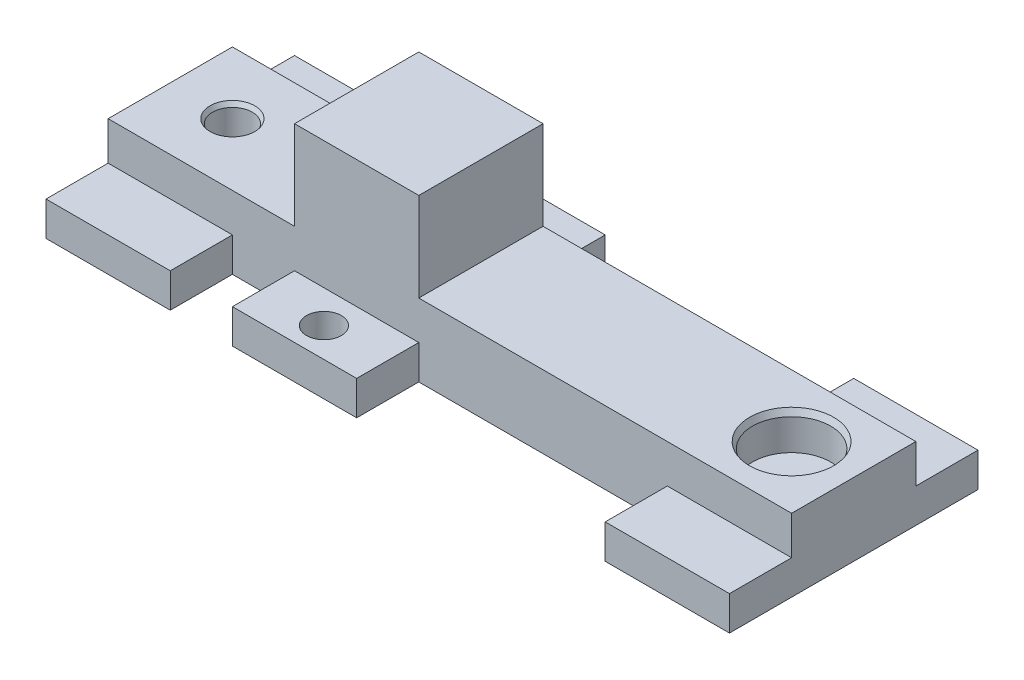
SolidWorks part; units mm, degrees
ref_plane "Front Plane" through (0, 0, 0) normal (0, 0, 1) x (1, 0, 0)
ref_plane "Top Plane" through (0, 0, 0) normal (0, 1, 0) x (1, 0, 0)
ref_plane "Right Plane" through (0, 0, 0) normal (1, 0, 0) x (0, 0, -1)
sketch "Sketch1" plane through (0, 0, 0) normal (0, 1, 0) x (1, 0, 0)
  line L1 (-20, 10) -> (35, 10)
  line L2 (-20, 10) -> (-20, -10)
  line L3 (-20, -10) -> (35, -10)
  line L4 (35, 10) -> (35, -10)
  dimension "D1" = 20
  dimension "D2" = 10
extrude "Boss-Extrude1" add sketch "Sketch1" along normal mid plane 13
sketch "Sketch2" plane through (0, 6.5, 0) normal (0, 1, 0) x (1, 0, 0)
  line L1 (35, 10) -> (-20, 10) construction
  line L2 (-20, -10) -> (35, -10) construction
  line L3 (-5, -10) -> (-20, -10)
  line L4 (-20, -10) -> (-20, 10)
  line L5 (-20, 10) -> (-5, 10)
  line L7 (5, -10) -> (35, -10)
  line L8 (35, -10) -> (35, 10)
  line L9 (35, 10) -> (5, 10)
  line L10 (-5, 5) -> (5, 5)
  line L11 (-5, -5) -> (5, -5)
  line L12 (-5, 10) -> (5, 10)
  line L13 (-5, -10) -> (5, -10)
  line L14 (-5, 5) -> (-5, -5)
  line L15 (5, 5) -> (5, -5)
  dimension "D3" = 5
  dimension "D4" = 5
extrude "Cut-Extrude3" cut sketch "Sketch2" against normal blind 7.15
sketch "Sketch6" plane through (0, -0.65, 0) normal (0, 1, 0) x (1, 0, 0)
  line L0 (-20, -5) -> (35, -5)
  line L1 (-20, 10) -> (-20, -10) construction
  line L2 (-5, 5) -> (-20, 5)
  line L3 (35, -10) -> (35, 10) construction
  line L4 (35, -5) -> (35, -10)
  line L5 (35, -10) -> (-20, -10)
  line L6 (-20, -10) -> (-20, -5)
  line L7 (-20, 5) -> (-20, 10)
  line L8 (-20, 10) -> (35, 10)
  line L9 (35, 10) -> (35, 5)
  line L10 (35, 5) -> (-5, 5)
extrude "Cut-Extrude4" cut sketch "Sketch6" against normal blind 3.1
sketch "Sketch7" plane through (0, -6.5, 0) normal (0, -1, 0) x (1, 0, 0)
  line L0 (-20, -10) -> (-20, 10) construction
  circle A0 centre (-15, 0) radius 1.6
  dimension "D1" = 5
extrude "Cut-Extrude5" cut sketch "Sketch7" against normal blind 10
sketch "Sketch9" plane through (0, -3.75, 0) normal (0, 1, 0) x (1, 0, 0)
  line L0 (-5, 5) -> (-5, 10)
  line L1 (35, 10) -> (-20, 10) construction
  line L2 (-5, 5) -> (-10, 5)
  line L3 (-20, 5) -> (35, 5) construction
  line L4 (-10, 5) -> (-10, 10)
  line L5 (-10, 10) -> (-5, 10)
  line L6 (-5, -5) -> (-5, -10)
  line L7 (35, -5) -> (-20, -5) construction
  line L8 (-5, -5) -> (5, -5) construction
  line L9 (-20, -10) -> (35, -10) construction
  line L10 (-5, -10) -> (-10, -10)
  line L11 (-10, -10) -> (-10, -5)
  line L12 (-5, -5) -> (-20, -5) construction
  line L13 (-10, -5) -> (-5, -5)
  line L14 (5, 5) -> (5, 10)
  line L15 (5, 10) -> (25, 10)
  line L16 (25, 10) -> (25, 5)
  line L17 (5, 5) -> (35, 5) construction
  line L18 (25, 5) -> (5, 5)
  line L19 (5, -5) -> (5, -10)
  line L20 (5, -5) -> (5, 5) construction
  line L21 (5, -10) -> (25, -10)
  line L22 (25, -10) -> (25, -5)
  line L23 (35, -5) -> (5, -5) construction
  line L24 (25, -5) -> (5, -5)
extrude "Cut-Extrude6" cut sketch "Sketch9" against normal blind 3
sketch "Sketch10" plane through (0, -3.75, 0) normal (0, 1, 0) x (1, 0, 0)
  line L5 (-20, 5) -> (-20, -5) construction
  line L6 (-20, 0) -> (35, 0)
  line L7 (35, -5) -> (35, 5) construction
  circle A1 centre (0, 7.6368) radius 1.4
  circle A2 centre (0, -7.6368) radius 1.4
extrude "Cut-Extrude7" cut sketch "Sketch10" against normal blind 3 contours A2 | A1
chamfer "Chamfer1" distance 0.2 angle 60 4 edges at (-15, -0.65, 1.6) (-15, -6.5, -1.6) (0, -6.5, 9.0368) (0, -6.5, -6.2368)
sketch "Sketch12" plane through (0, -0.65, 0) normal (0, 1, 0) x (1, 0, 0)
  line L0 (35, -5) -> (35, 5) construction
  circle A0 centre (30, 0) radius 3.15
  dimension "D1" = 5
extrude "Cut-Extrude8" cut sketch "Sketch12" against normal blind 3
chamfer "Chamfer2" distance 0.5 angle 25 1 edges at (30, -0.65, 3.15)
